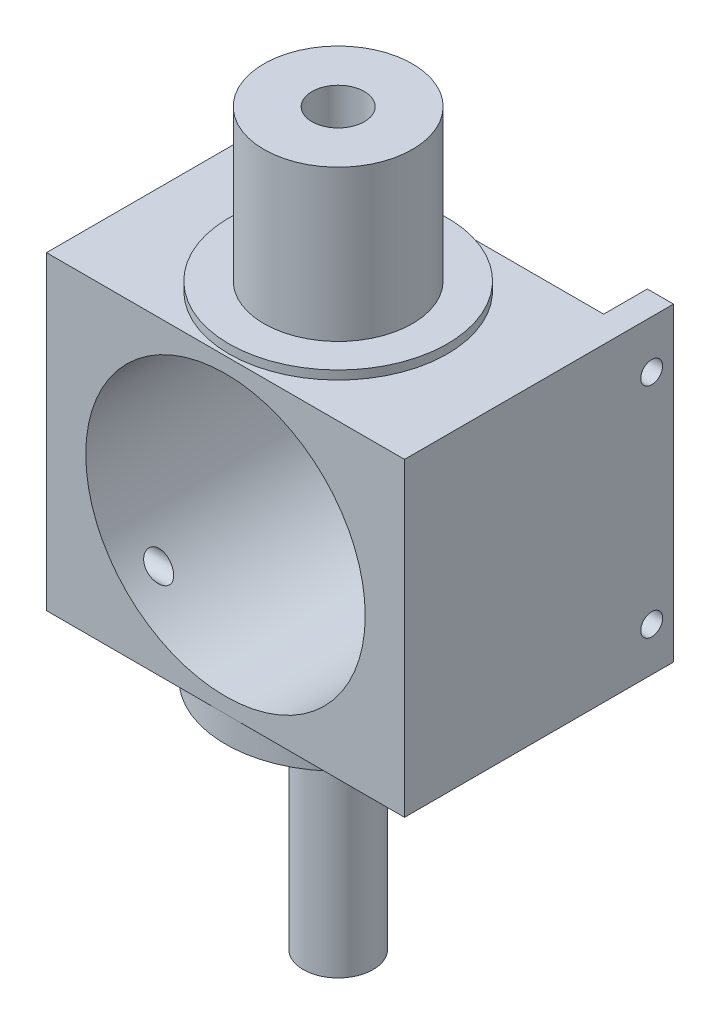
SolidWorks part; units mm, degrees
ref_plane "Front Plane" through (0, 0, 0) normal (0, 0, 1) x (1, 0, 0)
ref_plane "Top Plane" through (0, 0, 0) normal (0, 1, 0) x (1, 0, 0)
ref_plane "Right Plane" through (0, 0, 0) normal (1, 0, 0) x (0, 0, -1)
sketch "Sketch1" plane through (0, 0, 0) normal (0, 0, 1) x (1, 0, 0)
  line L0 (15.4, 41) -> (-15.4, 41)
  line L1 (-15.4, 41) -> (-15.4, 0)
  line L2 (15.4, 41) -> (15.4, 38)
  line L3 (15.4, 38) -> (10.4, 38)
  line L4 (10.4, 38) -> (10.4, 3)
  line L5 (10.4, 3) -> (15.4, 3)
  line L6 (15.4, 3) -> (15.4, 0)
  line L7 (15.4, 0) -> (-15.4, 0)
  dimension "D1" = 41
  dimension "D2" = 35
  dimension "D3" = 30.8
  dimension "D4" = 25.8
extrude "Boss-Extrude1" add sketch "Sketch1" along normal blind 35.5
sketch "Sketch2" plane through (0, 0, 35.5) normal (0, 0, 1) x (1, 0, 0)
  line L0 (-15.4, 41) -> (-15.4, 0) construction
  circle A0 centre (-2.5, 20.5) radius 12.9
  point P4 (-15.4, 20.5)
  dimension "D1" = 25.8
extrude "Boss-Extrude2" add sketch "Sketch2" along normal blind 3
sketch "Sketch3" plane through (0, 0, 38.5) normal (0, 0, 1) x (1, 0, 0)
  circle A0 centre (-2.5, 20.5) radius 4
  dimension "D1" = 8
extrude "Boss-Extrude3" add sketch "Sketch3" along normal blind 26.8
sketch "Sketch4" plane through (0, 0, 0) normal (0, 0, -1) x (-1, 0, 0)
  circle A0 centre (2.5, 20.5) radius 12.5
  dimension "D1" = 25
extrude "Boss-Extrude4" add sketch "Sketch4" along normal blind 1
sketch "Sketch5" plane through (0, 0, -1) normal (0, 0, -1) x (-1, 0, 0)
  circle A0 centre (2.5, 20.5) radius 8.5
  dimension "D1" = 17
extrude "Boss-Extrude5" add sketch "Sketch5" along normal blind 17.28
sketch "Sketch6" plane through (10.4, 0, 0) normal (1, 0, 0) x (0, 0, -1)
  line L0 (-35.5, 3) -> (0, 3) construction
  circle A0 centre (-17.75, 20.5) radius 16
  point P4 (-17.75, 3)
  dimension "D1" = 32
extrude "Cut-Extrude1" cut sketch "Sketch6" against normal up to next
sketch "Sketch7" plane through (0, 0, -18.28) normal (0, 0, -1) x (-1, 0, 0)
  circle A0 centre (2.5, 20.5) radius 3
  dimension "D1" = 6
extrude "Cut-Extrude2" cut sketch "Sketch7" against normal up to next
sketch "Sketch8" plane through (0, 0, 0) normal (0, -1, 0) x (1, 0, 0)
  line L0 (1.5, 65.3) -> (-6.5, 65.3) construction
  line L1 (-15.4, 35.5) -> (-15.4, 0) construction
  line L2 (15.4, 35.5) -> (15.4, 0) construction
  circle A0 centre (12.9, 30.5) radius 1.25
  circle A1 centre (12.9, 5.5) radius 1.25
  circle A2 centre (9.4, 18.45) radius 1.25
  circle A3 centre (-11.4, 28.65) radius 1.25
  dimension "D5" = 2.5
  dimension "D6" = 2.5
  dimension "D7" = 2.5
  dimension "D8" = 2.5
  dimension "D1" = 59.8
  dimension "D2" = 46.85
  dimension "D3" = 34.8
  dimension "D4" = 36.65
  dimension "D9" = 28.3
  dimension "D10" = 4
  dimension "D11" = 6
extrude "Cut-Extrude3" cut sketch "Sketch8" against normal up to next
sketch "Sketch9" plane through (0, 38, 0) normal (0, -1, 0) x (1, 0, 0)
  circle A0 centre (12.9, 30.5) radius 1.25
  circle A1 centre (12.9, 5.5) radius 1.25
extrude "Cut-Extrude4" cut sketch "Sketch9" against normal up to next
ref_plane "Plane1" through (0, 0, 17.75) normal (0, 0, 1) x (1, 0, 0)
sketch "Sketch10" plane through (0, 0, 17.75) normal (0, 0, 1) x (1, 0, 0)
  point P0 (-2.5, 20.5)
move or copy body "Body-Move/Copy1" bodies to move or copy 109 copy no translate (2.5, -20.5, -17.75) parameters "D1"=0, "D2"=0, "D3"=0
move or copy body "Body-Move/Copy2" bodies to move or copy 111 copy no rotation origin (0, 0, 0) rotation axis (0.5774, 0.5774, -0.5774) rotation angle 120
